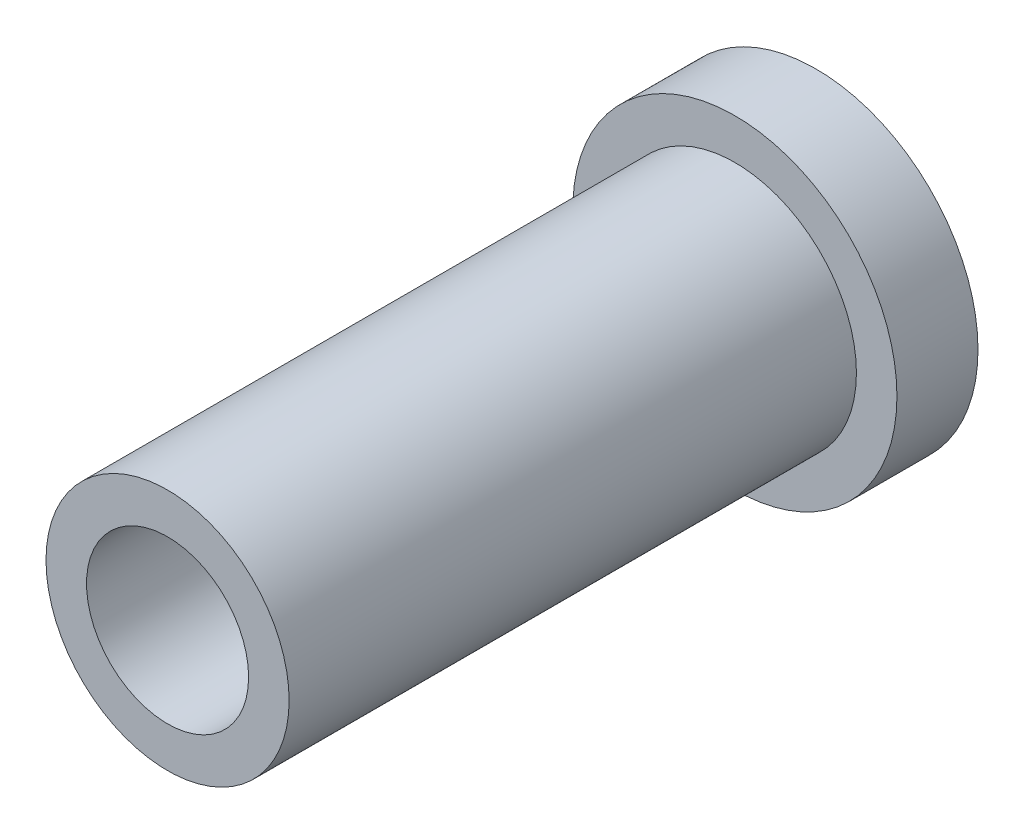
SolidWorks part; units mm, degrees
ref_plane "Plan de face" through (0, 0, 0) normal (0, 0, 1) x (1, 0, 0)
ref_plane "Plan de dessus" through (0, 0, 0) normal (0, 1, 0) x (1, 0, 0)
ref_plane "Plan de droite" through (0, 0, 0) normal (1, 0, 0) x (0, 0, -1)
sketch "Esquisse1" plane through (0, 0, 0) normal (0, 0, 1) x (1, 0, 0)
  circle A0 centre (1.3739, 0.602) radius 4 construction
  circle A1 centre (1.3739, 0.602) radius 4
  circle A2 centre (1.3739, 0.602) radius 2
  dimension "D1" = 4
extrude "Boss.-Extru.1" add sketch "Esquisse1" along normal blind 2
sketch "Esquisse2" plane through (0, 0, 2) normal (0, 0, 1) x (1, 0, 0)
  circle A0 centre (1.3739, 0.602) radius 3
  circle A1 centre (1.3739, 0.602) radius 2
  dimension "D1" = 6
  dimension "D2" = 4
extrude "Boss.-Extru.2" add sketch "Esquisse2" along normal blind 14
